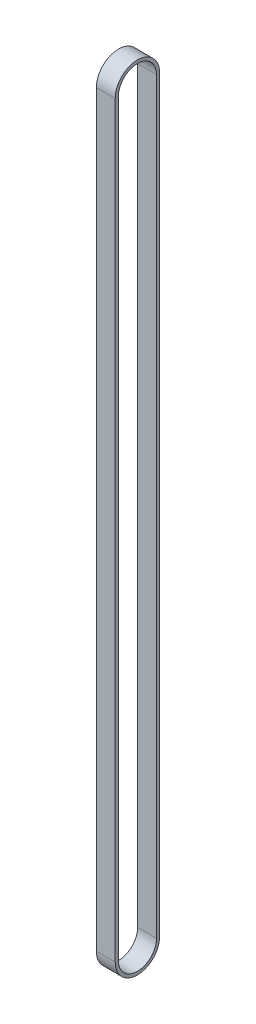
SolidWorks part; units mm, degrees
material "6063-T5"
ref_plane "Front Plane" through (0, 0, 0) normal (1, 0, 0) x (0, 1, 0)
ref_plane "Top Plane" through (0, 0, 0) normal (0, 0, 1) x (0, 1, 0)
ref_plane "Right Plane" through (0, 0, 0) normal (0, 1, 0) x (-1, 0, 0)
sketch "Sketch1" plane through (0, 0, 0) normal (1, 0, 0) x (0, 1, 0)
  line L0 (-120, 0) -> (120, 0) construction
  line L1 (-120, 6.125) -> (120, 6.125)
  line L2 (-120, -6.125) -> (120, -6.125)
  line L3 (-120, 7.125) -> (120, 7.125)
  line L4 (-120, -7.125) -> (120, -7.125)
  arc A0 (-120, 6.125) -> (-120, -6.125) centre (-120, 0) ccw
  arc A1 (120, -6.125) -> (120, 6.125) centre (120, 0) ccw
  arc A2 (120, -7.125) -> (120, 7.125) centre (120, 0) ccw
  arc A3 (-120, 7.125) -> (-120, -7.125) centre (-120, 0) ccw
  point P2 (0, 0)
  dimension "D2" = 6.125
  dimension "D1" = 240
  dimension "D3" = 1
extrude "Boss-Extrude1" add sketch "Sketch1" along normal blind 6.05
